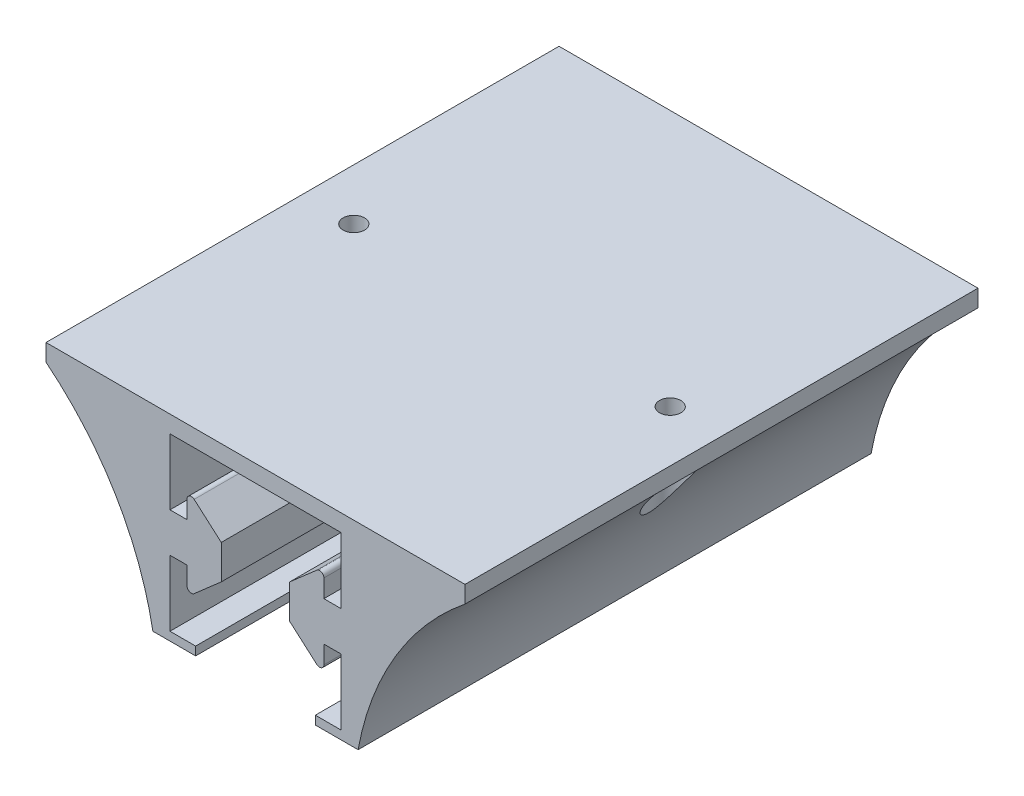
SolidWorks part; units mm, degrees
ref_plane "Front Plane" through (0, 0, 0) normal (0, 0, 1) x (1, 0, 0)
ref_plane "Top Plane" through (0, 0, 0) normal (0, 1, 0) x (1, 0, 0)
ref_plane "Right Plane" through (0, 0, 0) normal (1, 0, 0) x (0, 0, -1)
sketch "Sketch1" plane through (0, 0, 0) normal (0, 0, 1) x (1, 0, 0)
  line L0 (12.7, 12.7) -> (-12.7, 12.7)
  line L1 (-12.7, 12.7) -> (-12.7, 2.921)
  line L2 (-12.7, 2.921) -> (-10.16, 2.921)
  line L3 (-10.16, 2.921) -> (-10.16, 5.5856)
  line L4 (-9.1068, 6.0635) -> (-5.08, 2.54)
  line L5 (-5.08, 2.54) -> (-5.08, -2.54)
  line L6 (-5.08, -2.54) -> (-9.1068, -6.0635)
  line L7 (-10.16, -5.5856) -> (-10.16, -2.921)
  line L8 (-10.16, -2.921) -> (-12.7, -2.921)
  line L9 (-12.7, -2.921) -> (-12.7, -12.7)
  line L10 (-12.7, -12.7) -> (-8.89, -12.7)
  line L11 (22.3999, 0) -> (-22.3999, 0) construction
  line L12 (15.24, 15.24) -> (-15.24, 15.24)
  line L13 (-15.24, 15.24) -> (-15.24, -13.97)
  line L14 (-15.24, -13.97) -> (-8.89, -13.97)
  line L15 (-8.89, -13.97) -> (-8.89, -12.7)
  line L16 (0, 0) -> (0, 4.6071) construction
  line L17 (8.89, -13.97) -> (8.89, -12.7)
  line L18 (15.24, -13.97) -> (8.89, -13.97)
  line L19 (15.24, 15.24) -> (15.24, -13.97)
  line L20 (12.7, -12.7) -> (8.89, -12.7)
  line L21 (12.7, -2.921) -> (12.7, -12.7)
  line L22 (10.16, -2.921) -> (12.7, -2.921)
  line L23 (10.16, -5.5856) -> (10.16, -2.921)
  line L24 (5.08, -2.54) -> (9.1068, -6.0635)
  line L25 (5.08, 2.54) -> (5.08, -2.54)
  line L26 (9.1068, 6.0635) -> (5.08, 2.54)
  line L27 (10.16, 2.921) -> (10.16, 5.5856)
  line L28 (12.7, 2.921) -> (10.16, 2.921)
  line L29 (12.7, 12.7) -> (12.7, 2.921)
  arc A0 (-9.1068, -6.0635) -> (-10.16, -5.5856) centre (-9.525, -5.5856) cw
  arc A1 (-10.16, 5.5856) -> (-9.1068, 6.0635) centre (-9.525, 5.5856) cw
  arc A2 (10.16, 5.5856) -> (9.1068, 6.0635) centre (9.525, 5.5856) ccw
  arc A3 (9.1068, -6.0635) -> (10.16, -5.5856) centre (9.525, -5.5856) ccw
  point P0 (10.16, 6.985)
  point P21 (-10.16, -6.985)
  point P24 (-10.16, 6.985)
  point P37 (0, 15.24)
  point P45 (0, 12.7)
  point P46 (10.16, -6.985)
  dimension "D8" = 0.635
  dimension "D1" = 12.7
  dimension "D2" = 12.7
  dimension "D3" = 5.842
  dimension "D4" = 5.08
  dimension "D5" = 13.97
  dimension "D6" = 5.08
  dimension "D7" = 2.54
  dimension "D9" = 1.27
  dimension "D10" = 2.54
  dimension "D11" = 2.54
  dimension "D12" = 6.35
extrude "Boss-Extrude1" add sketch "Sketch1" along normal mid plane 76.2
sketch "Sketch6" plane through (0, 0, -38.1) normal (0, 0, -1) x (-1, 0, 0)
  line L0 (0, 0) -> (0, 15.9945) construction
  line L1 (-15.24, 15.24) -> (-31.115, 15.24)
  line L2 (-15.24, 15.24) -> (-15.24, -13.97)
  line L3 (15.24, 15.24) -> (31.115, 15.24)
  line L4 (-31.115, 15.24) -> (-31.115, 12.7)
  line L5 (31.115, 15.24) -> (31.115, 12.7)
  line L6 (15.24, 15.24) -> (15.24, -13.97)
  arc A0 (-31.115, 12.7) -> (-15.24, -13.97) centre (-58.9697, -21.9399) cw
  arc A1 (31.115, 12.7) -> (15.24, -13.97) centre (58.9697, -21.9399) ccw
  dimension "D2" = 44.45
  dimension "D1" = 15.875
  dimension "D3" = 2.54
extrude "Boss-Extrude3" add sketch "Sketch6" against normal up to surface (76.2 mm away) up to face at (0, -1.5875, 38.1)
ref_plane "Plane1" through (0, 2.54, 0) normal (0, 1, 0) x (1, 0, 0)
sketch "Sketch4" plane through (0, 2.54, 0) normal (0, 1, 0) x (1, 0, 0)
  line L0 (0, 0) -> (0, -70.3147) construction
  circle A0 centre (23.495, 0) radius 3.175
  point P5 (0, -13.4295)
  point P6 (23.8632, -1.1247)
  dimension "D2" = 6.35
  dimension "D1" = 23.495
extrude "Cut-Extrude1" cut sketch "Sketch4" against normal up to next and the other way blind 6.35
sketch "Sketch5" plane through (0, 8.89, 0) normal (0, -1, 0) x (1, 0, 0)
  circle A0 centre (23.495, 0) radius 1.5875
  circle A2 centre (23.495, 0) radius 3.175 construction
  dimension "D1" = 3.175
extrude "Cut-Extrude2" cut sketch "Sketch5" against normal up to next
mirror "Mirror1" about plane through (0, 0, 0) normal (1, 0, 0) of "Cut-Extrude2", "Cut-Extrude1"
